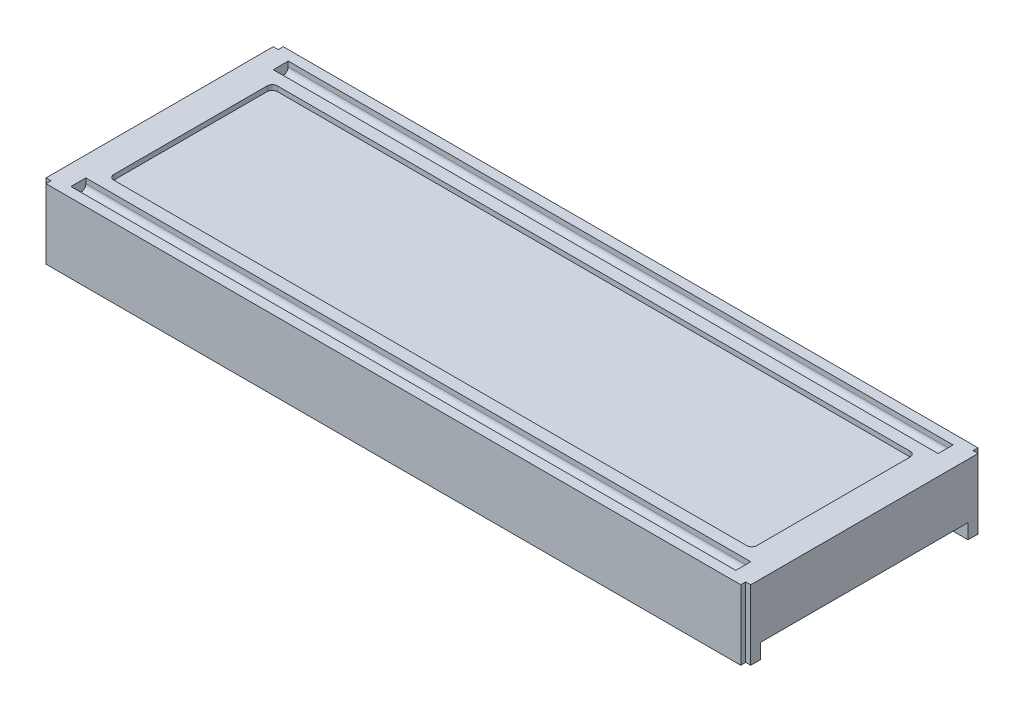
SolidWorks part; units mm, degrees
ref_plane "Alzado" through (0, 0, 0) normal (0, 0, 1) x (1, 0, 0)
ref_plane "Planta" through (0, 0, 0) normal (0, 1, 0) x (1, 0, 0)
ref_plane "Vista lateral" through (0, 0, 0) normal (1, 0, 0) x (0, 0, -1)
sketch "Croquis1" plane through (0, 0, 0) normal (0, 1, 0) x (1, 0, 0)
  line L1 (-35.35, -11.9) -> (35.35, -11.9)
  line L2 (-35.35, -11.9) -> (-35.35, 11.9)
  line L3 (-35.35, 11.9) -> (35.35, 11.9)
  line L4 (35.35, -11.9) -> (35.35, 11.9)
  line L5 (-35.35, -11.9) -> (35.35, 11.9) construction
  line L6 (-35.35, 11.9) -> (35.35, -11.9) construction
  point P0 (0, 0)
  dimension "D1" = 70.7
  dimension "D2" = 23.8
extrude "Saliente-Extruir1" add sketch "Croquis1" along normal blind 7
sketch "Croquis2" plane through (0, 7, 0) normal (0, 1, 0) x (1, 0, 0)
  line L1 (-32.25, -8.2) -> (32.25, -8.2)
  line L2 (-32.25, -8.2) -> (-32.25, 8.2)
  line L3 (-32.25, 8.2) -> (32.25, 8.2)
  line L4 (32.25, -8.2) -> (32.25, 8.2)
  line L5 (-32.25, -8.2) -> (32.25, 8.2) construction
  line L6 (-32.25, 8.2) -> (32.25, -8.2) construction
  point P0 (0, 0)
  dimension "D1" = 64.5
  dimension "D2" = 16.4
extrude "Cortar-Extruir1" cut sketch "Croquis2" against normal blind 0.5 contours L3 L4 L1 L2
fillet "Redondeo1" radius 0.5 4 edges at (32.25, 6.75, -8.2) (32.25, 6.75, 8.2) (-32.25, 6.75, 8.2) (-32.25, 6.75, -8.2)
sketch "Croquis3" plane through (0, 7, 0) normal (0, 1, 0) x (1, 0, 0)
  line L1 (-35.35, 11.9) -> (-34.85, 11.9)
  line L2 (-35.35, 11.9) -> (-35.35, 11.4)
  line L3 (-35.35, 11.4) -> (-34.85, 11.4)
  line L4 (-34.85, 11.9) -> (-34.85, 11.4)
  line L5 (-35.35, -11.9) -> (-34.85, -11.9)
  line L6 (-35.35, -11.9) -> (-35.35, -11.4)
  line L7 (-35.35, -11.4) -> (-34.85, -11.4)
  line L8 (-34.85, -11.9) -> (-34.85, -11.4)
  line L9 (35.35, -11.9) -> (34.85, -11.9)
  line L10 (35.35, -11.9) -> (35.35, -11.4)
  line L11 (35.35, -11.4) -> (34.85, -11.4)
  line L12 (34.85, -11.9) -> (34.85, -11.4)
  line L13 (35.35, 11.9) -> (34.85, 11.9)
  line L14 (35.35, 11.9) -> (35.35, 11.4)
  line L15 (35.35, 11.4) -> (34.85, 11.4)
  line L16 (34.85, 11.9) -> (34.85, 11.4)
  dimension "D1" = 0.5
  dimension "D2" = 0.5
extrude "Cortar-Extruir2" cut sketch "Croquis3" against normal blind 7
sketch "Croquis4" plane through (0, 0, 0) normal (0, -1, 0) x (1, 0, 0)
  line L0 (-34.85, 11.9) -> (34.85, 11.9) construction
  line L1 (-35.35, -10.4) -> (35.35, -10.4)
  line L2 (-35.35, -10.4) -> (-35.35, 10.4)
  line L3 (-35.35, 10.4) -> (35.35, 10.4)
  line L4 (35.35, -10.4) -> (35.35, 10.4)
  line L5 (-35.35, -10.4) -> (35.35, 10.4) construction
  line L6 (-35.35, 10.4) -> (35.35, -10.4) construction
  line L7 (35.35, 11.4) -> (35.35, -11.4) construction
  point P0 (0, 0)
  dimension "D1" = 1.5
extrude "Cortar-Extruir3" cut sketch "Croquis4" against normal blind 1.5
sketch "Croquis5" plane through (0, 7, 0) normal (0, 1, 0) x (1, 0, 0)
  line L0 (-34.85, -11.9) -> (34.85, -11.9) construction
  line L1 (-33.35, 9.4) -> (33.35, 9.4)
  line L2 (-33.35, 9.4) -> (-33.35, 10.9)
  line L3 (-33.35, 10.9) -> (33.35, 10.9)
  line L4 (33.35, 9.4) -> (33.35, 10.9)
  line L5 (-33.35, -9.4) -> (33.35, -9.4)
  line L6 (-33.35, -9.4) -> (-33.35, -10.9)
  line L7 (-33.35, -10.9) -> (33.35, -10.9)
  line L8 (33.35, -9.4) -> (33.35, -10.9)
  line L9 (34.85, 11.9) -> (-34.85, 11.9) construction
  line L10 (-35.35, 11.4) -> (-35.35, -11.4) construction
  line L11 (35.35, -11.4) -> (35.35, 11.4) construction
  dimension "D1" = 1.5
  dimension "D2" = 1
  dimension "D3" = 1.5
  dimension "D4" = 1
  dimension "D5" = 2
  dimension "D6" = 2
extrude "Cortar-Extruir4" cut sketch "Croquis5" against normal blind 1
fillet "Redondeo2" radius 0.5 4 edges at (0, 6, 10.9) (0, 6, 9.4) (0, 6, -9.4) (0, 6, -10.9)
